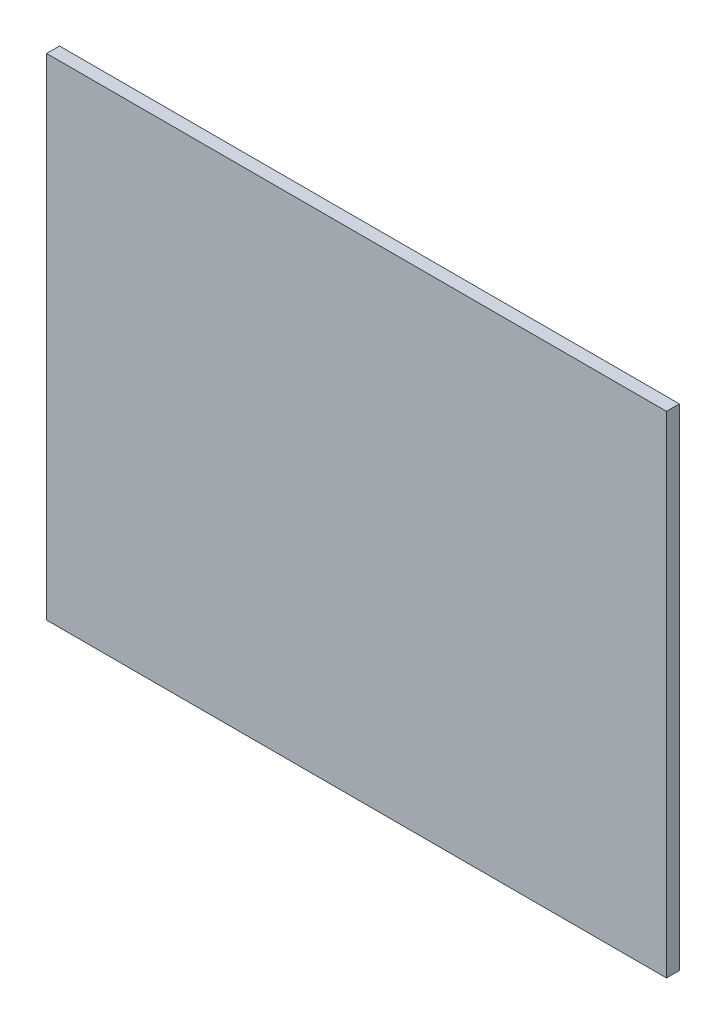
SolidWorks part; units mm, degrees
ref_plane "Plan de face" through (0, 0, 0) normal (0, 0, 1) x (1, 0, 0)
ref_plane "Plan de dessus" through (0, 0, 0) normal (0, 1, 0) x (1, 0, 0)
ref_plane "Plan de droite" through (0, 0, 0) normal (1, 0, 0) x (0, 0, -1)
sketch "Esquisse1" plane through (0, 0, 0) normal (0, 0, 1) x (1, 0, 0)
  line L1 (0, 0) -> (240, 0)
  line L2 (0, 0) -> (0, -190)
  line L3 (0, -190) -> (240, -190)
  line L4 (240, 0) -> (240, -190)
  point P5 (250, -214.2963)
  dimension "D1" = 240
  dimension "D2" = 190
extrude "Boss.-Extru.1" add sketch "Esquisse1" along normal blind 5
sketch "Esquisse2" plane through (0, 0, 5) normal (0, 0, 1) x (1, 0, 0)
  line L0 (120, 0) -> (120, -190) construction
  line L1 (240, 0) -> (0, 0) construction
  line L2 (0, -190) -> (240, -190) construction
  line L3 (0, -95) -> (240, -95) construction
  line L4 (0, 0) -> (0, -190) construction
  line L5 (240, -190) -> (240, 0) construction
  circle A0 centre (9.6687, -10.0958) radius 3
  dimension "D1" = 6
